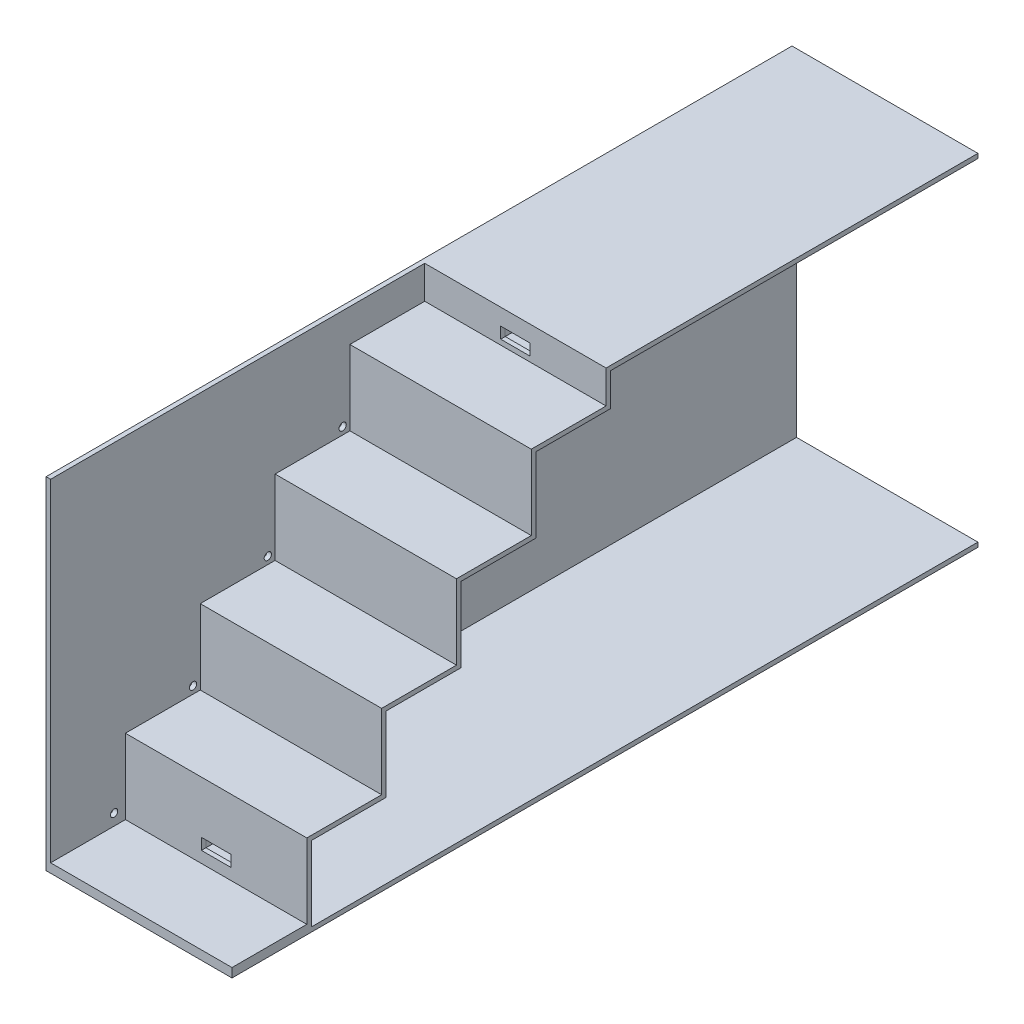
SolidWorks part; units mm, degrees
ref_plane "Front Plane" through (0, 0, 0) normal (0, 0, 1) x (1, 0, 0)
ref_plane "Top Plane" through (0, 0, 0) normal (0, 1, 0) x (1, 0, 0)
ref_plane "Right Plane" through (0, 0, 0) normal (1, 0, 0) x (0, 0, -1)
sketch "Sketch1" plane through (0, 0, 0) normal (1, 0, 0) x (0, 0, -1)
  line L0 (-23.9317, -26.5974) -> (-23.9317, 6.4026)
  line L1 (-25.9317, -24.5974) -> (-25.9317, 8.4026)
  line L3 (-25.9317, 8.4026) -> (7.0683, 8.4026)
  line L4 (-23.9317, 6.4026) -> (9.0683, 6.4026)
  line L6 (9.0683, 6.4026) -> (9.0683, 39.4026)
  line L7 (-23.9317, -26.5974) -> (-23.9317, 8.4026) construction
  line L8 (-25.9317, 6.4026) -> (9.0683, 6.4026) construction
  line L9 (7.0683, 8.4026) -> (7.0683, 41.4026)
  line L12 (-25.9317, 8.4026) -> (9.0683, 8.4026) construction
  line L13 (7.0683, 6.4026) -> (7.0683, 41.4026) construction
  line L14 (9.0683, 39.4026) -> (42.0683, 39.4026)
  line L16 (7.0683, 41.4026) -> (40.0683, 41.4026)
  line L17 (9.0683, 6.4026) -> (9.0683, 41.4026) construction
  line L18 (-23.9317, -26.5974) -> (-58.9317, -26.5974)
  line L19 (-25.9317, -24.5974) -> (-58.9317, -24.5974)
  line L20 (-58.9317, -24.5974) -> (-58.9317, -26.5974)
  line L22 (-25.9317, -26.5974) -> (-25.9317, 8.4026) construction
  line L23 (-23.9317, -24.5974) -> (-58.9317, -24.5974) construction
  line L24 (40.0683, 41.4026) -> (40.0683, 74.4026)
  line L26 (42.0683, 39.4026) -> (42.0683, 72.4026)
  line L27 (40.0683, 74.4026) -> (73.0683, 74.4026)
  line L28 (42.0683, 72.4026) -> (75.0683, 72.4026)
  line L30 (40.0683, 72.4026) -> (75.0683, 72.4026) construction
  line L31 (75.0683, 72.4026) -> (75.0683, 105.4026)
  line L32 (73.0683, 74.4026) -> (73.0683, 107.4026)
  line L34 (73.0683, 107.4026) -> (106.0683, 107.4026)
  line L35 (40.0683, 74.4026) -> (75.0683, 74.4026) construction
  line L36 (73.0683, 72.4026) -> (73.0683, 107.4026) construction
  line L37 (75.0683, 105.4026) -> (108.0683, 105.4026)
  line L39 (108.0683, 105.4026) -> (108.0683, 138.4026)
  line L40 (73.0683, 105.4026) -> (108.0683, 105.4026) construction
  line L41 (75.0683, 72.4026) -> (75.0683, 107.4026) construction
  line L42 (106.0683, 107.4026) -> (106.0683, 140.4026)
  line L44 (106.0683, 140.4026) -> (139.0683, 140.4026)
  line L45 (73.0683, 107.4026) -> (108.0683, 107.4026) construction
  line L46 (106.0683, 105.4026) -> (106.0683, 140.4026) construction
  line L47 (108.0683, 138.4026) -> (141.0683, 138.4026)
  line L49 (141.0683, 138.4026) -> (141.0683, 171.4026)
  line L50 (108.0683, 105.4026) -> (108.0683, 140.4026) construction
  line L51 (106.0683, 138.4026) -> (141.0683, 138.4026) construction
  line L52 (139.0683, 140.4026) -> (139.0683, 173.4026)
  line L54 (139.0683, 173.4026) -> (172.0683, 173.4026)
  line L55 (106.0683, 140.4026) -> (141.0683, 140.4026) construction
  line L56 (139.0683, 138.4026) -> (139.0683, 173.4026) construction
  line L57 (141.0683, 171.4026) -> (174.0683, 171.4026)
  line L59 (174.0683, 171.4026) -> (174.0683, 204.4026)
  line L60 (141.0683, 138.4026) -> (141.0683, 173.4026) construction
  line L61 (139.0683, 171.4026) -> (174.0683, 171.4026) construction
  line L62 (172.0683, 173.4026) -> (172.0683, 206.4026)
  line L64 (172.0683, 206.4026) -> (205.0683, 206.4026)
  line L65 (139.0683, 173.4026) -> (174.0683, 173.4026) construction
  line L66 (172.0683, 171.4026) -> (172.0683, 206.4026) construction
  line L67 (174.0683, 204.4026) -> (207.0683, 204.4026)
  line L69 (207.0683, 204.4026) -> (207.0683, 237.4026)
  line L70 (174.0683, 171.4026) -> (174.0683, 206.4026) construction
  line L71 (172.0683, 204.4026) -> (207.0683, 204.4026) construction
  line L72 (205.0683, 206.4026) -> (205.0683, 239.4026)
  line L74 (205.0683, 239.4026) -> (238.0683, 239.4026)
  line L75 (172.0683, 206.4026) -> (207.0683, 206.4026) construction
  line L76 (205.0683, 204.4026) -> (205.0683, 239.4026) construction
  line L77 (207.0683, 237.4026) -> (240.0683, 237.4026)
  line L79 (240.0683, 237.4026) -> (240.0683, 272.4026)
  line L80 (207.0683, 204.4026) -> (207.0683, 239.4026) construction
  line L81 (205.0683, 237.4026) -> (240.0683, 237.4026) construction
  line L82 (238.0683, 239.4026) -> (238.0683, 272.4026)
  line L83 (238.0683, 272.4026) -> (240.0683, 272.4026)
  line L85 (205.0683, 239.4026) -> (240.0683, 239.4026) construction
  line L86 (238.0683, 237.4026) -> (238.0683, 272.4026) construction
  point P12 (7.0683, 39.4026)
  point P13 (42.0683, 41.4026)
  point P20 (40.0683, 39.4026)
  dimension "D3" = 35
  dimension "D5" = 2
  dimension "D7" = 35
  dimension "D8" = 2
  dimension "D9" = 299
  dimension "D10" = 35
  dimension "D21" = 35
  dimension "D1" = 2
  dimension "D4" = 2
  dimension "D6" = 2
  dimension "D11" = 2
  dimension "D12" = 2
  dimension "D13" = 2
  dimension "D14" = 2
  dimension "D15" = 2
  dimension "D16" = 2
  dimension "D17" = 2
  dimension "D18" = 2
  dimension "D19" = 2
  dimension "D20" = 2
  dimension "D22" = 2
extrude "Boss-Extrude1" add sketch "Sketch1" along normal blind 80
sketch "Sketch3" plane through (0, 0, 0) normal (-1, 0, 0) x (0, 0, 1)
  line L1 (-240.0683, 272.4026) -> (58.9317, 272.4026)
  line L2 (-240.0683, 272.4026) -> (-240.0683, -26.5974)
  line L3 (-240.0683, -26.5974) -> (58.9317, -26.5974)
  line L4 (58.9317, 272.4026) -> (58.9317, -26.5974)
extrude "Boss-Extrude2" add sketch "Sketch3" along normal blind 2
sketch "Sketch4" plane through (0, -26.5974, 0) normal (0, -1, 0) x (1, 0, 0)
  line L0 (80, -207.0683) -> (80, -240.0683) construction
  line L1 (-2, 58.9317) -> (80, 58.9317)
  line L2 (-2, 58.9317) -> (-2, -240.0683)
  line L3 (-2, -240.0683) -> (80, -240.0683)
  line L4 (80, 58.9317) -> (80, -240.0683)
extrude "Boss-Extrude3" add sketch "Sketch4" along normal blind 2
sketch "Sketch6" plane through (-2, 0, 0) normal (-1, 0, 0) x (0, 0, 1)
  line L0 (-240.0683, 121.9026) -> (58.9317, 121.9026) construction
  line L1 (-240.0683, 272.4026) -> (-240.0683, -28.5974) construction
  line L2 (58.9317, -28.5974) -> (58.9317, 272.4026) construction
  line L4 (58.9317, 121.9026) -> (-240.0683, 121.9026)
  line L5 (58.9317, 121.9026) -> (58.9317, 272.4026)
  line L6 (58.9317, 272.4026) -> (-240.0683, 272.4026)
  line L7 (-240.0683, 121.9026) -> (-240.0683, 272.4026)
extrude "Cut-Extrude1" cut sketch "Sketch6" against normal up to surface (82 mm away) up to face at (80, 107.9526, -105.4183)
sketch "Sketch7" plane through (0, 0, 0) normal (1, 0, 0) x (0, 0, -1)
  line L0 (240.0683, 121.9026) -> (240.0683, -26.5974) construction
  line L1 (108.0683, 121.9026) -> (240.0683, 121.9026)
  line L2 (108.0683, 121.9026) -> (108.0683, 119.9026)
  line L3 (108.0683, 119.9026) -> (240.0683, 119.9026)
  line L4 (240.0683, 121.9026) -> (240.0683, 119.9026)
  dimension "D1" = 2
extrude "Boss-Extrude5" add sketch "Sketch7" along normal up to surface (80 mm away) up to face at (80, 41.4443, -49.3183)
sketch "Sketch8" plane through (0, 0, 0) normal (1, 0, 0) x (0, 0, -1)
  line L0 (-25.9317, -24.5974) -> (-58.9317, -24.5974) construction
  line L1 (-25.9317, 8.4026) -> (-25.9317, -24.5974) construction
  line L2 (7.0683, 8.4026) -> (-25.9317, 8.4026) construction
  line L3 (7.0683, 41.4026) -> (7.0683, 8.4026) construction
  line L4 (40.0683, 41.4026) -> (7.0683, 41.4026) construction
  line L5 (40.0683, 74.4026) -> (40.0683, 41.4026) construction
  line L6 (73.0683, 74.4026) -> (40.0683, 74.4026) construction
  line L7 (73.0683, 107.4026) -> (73.0683, 74.4026) construction
  circle A0 centre (-30.9317, -19.5974) radius 1.6
  circle A1 centre (3.8683, 11.6026) radius 1.6
  circle A2 centre (36.8683, 44.6026) radius 1.6
  circle A3 centre (69.8683, 77.6026) radius 1.6
  dimension "D1" = 3.2
  dimension "D2" = 3.2
  dimension "D3" = 3.2
  dimension "D4" = 3.2
  dimension "D5" = 5
  dimension "D6" = 5
  dimension "D7" = 3.2
  dimension "D8" = 3.2
  dimension "D9" = 3.2
  dimension "D10" = 3.2
  dimension "D11" = 3.2
  dimension "D12" = 3.2
extrude "Cut-Extrude2" cut sketch "Sketch8" against normal up to surface (2 mm away) up to face at (-2, 46.6526, -90.5683)
sketch "Sketch9" plane through (0, 0, 25.9317) normal (0, 0, 1) x (1, 0, 0)
  line L0 (40, -24.5974) -> (40, 121.9026) construction
  line L1 (80, -24.5974) -> (0, -24.5974) construction
  line L2 (80, 121.9026) -> (0, 121.9026) construction
  line L4 (33.5, -14.5974) -> (46.5, -14.5974)
  line L5 (33.5, -14.5974) -> (33.5, -19.5974)
  line L6 (33.5, -19.5974) -> (46.5, -19.5974)
  line L7 (46.5, -14.5974) -> (46.5, -19.5974)
  line L8 (33.5, -14.5974) -> (46.5, -19.5974) construction
  line L9 (33.5, -19.5974) -> (46.5, -14.5974) construction
  line L14 (33.5, 18.4026) -> (46.5, 13.4026) construction
  line L15 (33.5, 13.4026) -> (46.5, 18.4026) construction
  line L21 (33.5, 49.0065) -> (46.5, 44.0065) construction
  line L22 (33.5, 44.0065) -> (46.5, 49.0065) construction
  line L27 (33.6237, 81.8385) -> (46.6237, 76.8385) construction
  line L28 (33.6237, 76.8385) -> (46.6237, 81.8385) construction
  line L29 (33.5, 114.6705) -> (46.5, 114.6705)
  line L30 (33.5, 114.6705) -> (33.5, 109.6705)
  line L31 (33.5, 109.6705) -> (46.5, 109.6705)
  line L32 (46.5, 114.6705) -> (46.5, 109.6705)
  line L33 (33.5, 114.6705) -> (46.5, 109.6705) construction
  line L34 (33.5, 109.6705) -> (46.5, 114.6705) construction
  point P6 (40, -17.0974)
  point P11 (40, 15.9026)
  point P18 (40, 46.5065)
  point P23 (40, 79.3861)
  point P28 (40, 112.1705)
  dimension "D1" = 13
  dimension "D2" = 5
  dimension "D3" = 5
  dimension "D4" = 13
  dimension "D5" = 5
  dimension "D7" = 13
  dimension "D8" = 5
  dimension "D9" = 5
  dimension "D10" = 5
  dimension "D11" = 13
  dimension "D12" = 13
extrude "Cut-Extrude3" cut sketch "Sketch9" against normal up to surface (266 mm away)
sketch "Sketch10" plane through (0, 0, 25.9317) normal (0, 0, 1) x (1, 0, 0)
  line L0 (33.5, -17.0974) -> (46.5, -17.0974) construction
  line L1 (33.5, -14.5974) -> (33.5, -19.5974) construction
  line L2 (46.5, -19.5974) -> (46.5, -14.5974) construction
  line L3 (40, -14.5974) -> (40, -19.5974) construction
  line L4 (46.5, -14.5974) -> (33.5, -14.5974) construction
  line L5 (33.5, -19.5974) -> (46.5, -19.5974) construction
  line L6 (31, -12.0974) -> (31, -22.0974)
  line L7 (33, -14.0974) -> (47, -14.0974)
  line L8 (33, -14.0974) -> (33, -20.0974)
  line L9 (33, -20.0974) -> (47, -20.0974)
  line L10 (47, -14.0974) -> (47, -20.0974)
  line L11 (33, -14.0974) -> (47, -20.0974) construction
  line L12 (33, -20.0974) -> (47, -14.0974) construction
  line L13 (31, -22.0974) -> (49, -22.0974)
  line L14 (49, -12.0974) -> (49, -22.0974)
  line L15 (31, -12.0974) -> (49, -12.0974)
  point P12 (40, -17.0974)
  dimension "D1" = 14
  dimension "D2" = 6
  dimension "D3" = 2
extrude "Boss-Extrude6" add sketch "Sketch10" against normal blind 10
sketch "Sketch11" plane through (0, 0, -108.0683) normal (0, 0, -1) x (-1, 0, 0)
  line L0 (-40, 114.6705) -> (-40, 109.6705) construction
  line L1 (-46.5, 114.6705) -> (-33.5, 114.6705) construction
  line L2 (-33.5, 109.6705) -> (-46.5, 109.6705) construction
  line L3 (-46.5, 112.1705) -> (-33.5, 112.1705) construction
  line L4 (-29.8862, 109.1149) -> (-29.7709, 109.1725) construction
  line L5 (-46.5, 109.6705) -> (-46.5, 114.6705) construction
  line L6 (-33.5, 114.6705) -> (-33.5, 109.6705) construction
  line L7 (-49, 117.1705) -> (-49, 107.1705)
  line L8 (-47, 115.1705) -> (-33, 115.1705)
  line L9 (-47, 115.1705) -> (-47, 109.1705)
  line L10 (-47, 109.1705) -> (-33, 109.1705)
  line L11 (-33, 115.1705) -> (-33, 109.1705)
  line L12 (-47, 115.1705) -> (-33, 109.1705) construction
  line L13 (-47, 109.1705) -> (-33, 115.1705) construction
  line L14 (-49, 107.1705) -> (-31, 107.1705)
  line L15 (-31, 117.1705) -> (-31, 107.1705)
  line L16 (-49, 117.1705) -> (-31, 117.1705)
  point P14 (-40, 112.1705)
  dimension "D1" = 6
  dimension "D2" = 14
  dimension "D3" = 2
extrude "Boss-Extrude7" add sketch "Sketch11" along normal blind 10
sketch "Sketch12" plane through (0, 0, -240.0683) normal (0, 0, -1) x (-1, 0, 0)
  line L8 (2, -28.5974) -> (2, 121.9026)
  line L9 (2, 121.9026) -> (-80, 121.9026)
  line L10 (-80, 121.9026) -> (-80, 119.9026)
  line L11 (-80, 119.9026) -> (0, 119.9026)
  line L12 (0, 119.9026) -> (0, -26.5974)
  line L13 (0, -26.5974) -> (-80, -26.5974)
  line L14 (-80, -26.5974) -> (-80, -28.5974)
  line L15 (-80, -28.5974) -> (2, -28.5974)
  line L16 (2, -28.5974) -> (2, 121.9026)
  line L17 (2, 121.9026) -> (-80, 121.9026)
  line L18 (-80, 121.9026) -> (-80, 119.9026)
  line L19 (-80, 119.9026) -> (0, 119.9026)
  line L20 (0, 119.9026) -> (0, -26.5974)
  line L21 (0, -26.5974) -> (-80, -26.5974)
  line L22 (-80, -26.5974) -> (-80, -28.5974)
  line L23 (-80, -28.5974) -> (2, -28.5974)
  dimension "D1" = 0
extrude "Boss-Extrude8" add sketch "Sketch12" along normal blind 30
